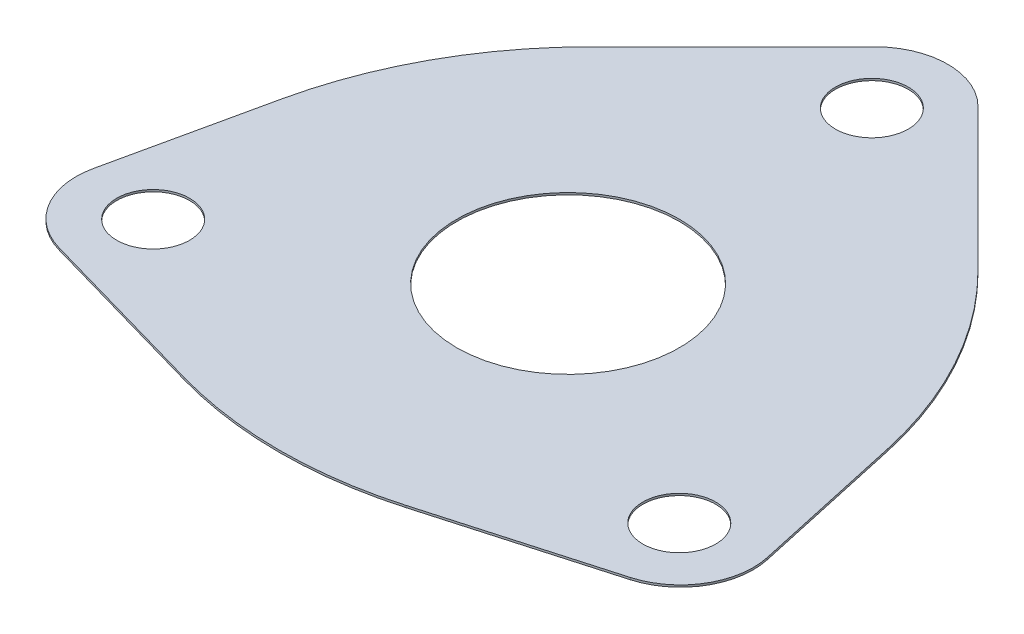
SolidWorks part; units mm, degrees
material "TESNIT BA-GL"
ref_plane "Front Plane" through (0, 0, 0) normal (0, 0, 1) x (1, 0, 0)
ref_plane "Top Plane" through (0, 0, 0) normal (0, 1, 0) x (1, 0, 0)
ref_plane "Right Plane" through (0, 0, 0) normal (1, 0, 0) x (0, 0, -1)
sketch "Sketch1" plane through (0, 0, 0) normal (0, 1, 0) x (1, 0, 0)
  line L0 (0, 0) -> (0, 40.3253) construction
  line L1 (0, 0) -> (35.9876, 0) construction
  line L2 (83.1843, -34.015) -> (74.8147, 4.0948)
  line L3 (-12.7279, 88.4801) -> (-47.8532, 53.3549)
  line L4 (12.7279, 88.4801) -> (47.8532, 53.3549)
  line L5 (70.534, -55.1876) -> (27.3925, -67.4751)
  line L6 (-70.534, -55.1876) -> (-27.3925, -67.4751)
  line L7 (-83.1843, -34.015) -> (-74.8147, 4.0948)
  line L8 (0, 0) -> (64.9519, -37.5) construction
  arc A0 (12.7279, 88.4801) -> (-12.7279, 88.4801) centre (0, 75.7522) ccw
  arc A1 (70.534, -55.1876) -> (83.1843, -34.015) centre (65.6033, -37.8761) ccw
  arc A2 (-83.1843, -34.015) -> (-70.534, -55.1876) centre (-65.6033, -37.8761) ccw
  arc A3 (27.3925, -67.4751) -> (-27.3925, -67.4751) centre (0, 28.7) cw
  arc A4 (74.8147, 4.0948) -> (47.8532, 53.3549) centre (-22.8575, -17.3558) ccw
  arc A5 (-74.8147, 4.0948) -> (-47.8532, 53.3549) centre (22.8575, -17.3558) cw
  circle A6 centre (0, 0) radius 75 construction
  circle A7 centre (64.9519, -37.5) radius 9
  circle A8 centre (-64.9519, -37.5) radius 9
  circle A9 centre (0, 75) radius 9
  circle A10 centre (0, 0) radius 27.5
  circle A11 centre (0, 0) radius 71.3 construction
  circle A12 centre (0, 0) radius 93.7522 construction
  dimension "D2" = 18
  dimension "D3" = 100
  dimension "D9" = 17.3558
  dimension "D10" = 150
  dimension "D12" = 18
  dimension "D13" = 55
  dimension "D4" = 142.6
  dimension "D1" = 90
  dimension "D5" = 120
extrude "Boss-Extrude1" add sketch "Sketch1" along normal blind 0.5
